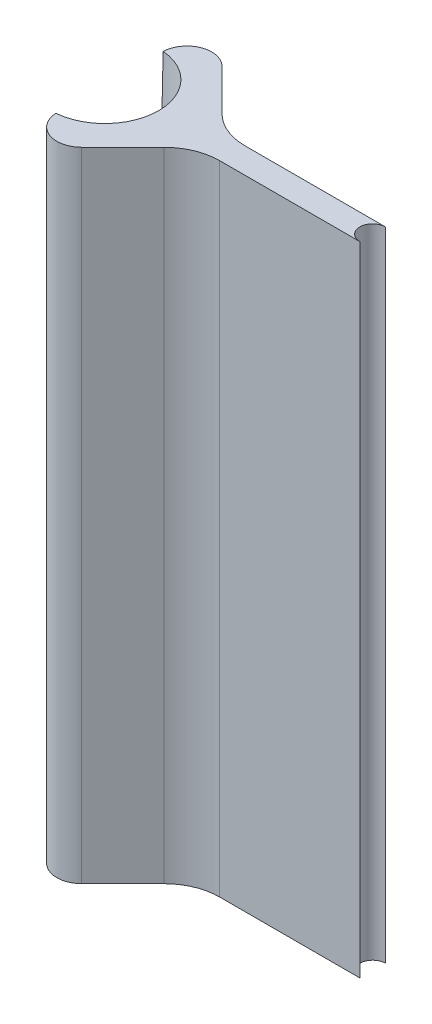
SolidWorks part; units mm, degrees
ref_plane "Front Plane" through (0, 0, 0) normal (0, 0, 1) x (1, 0, 0)
ref_plane "Top Plane" through (0, 0, 0) normal (0, 1, 0) x (1, 0, 0)
ref_plane "Right Plane" through (0, 0, 0) normal (1, 0, 0) x (0, 0, -1)
sketch "Sketch2" plane through (0, 0, 0) normal (0, 1, 0) x (1, 0, 0)
  line L0 (0, 0) -> (4, 0) construction
  line L1 (0, 0) -> (0.0553, 0.6326) construction
  line L2 (0.0553, 0.6326) -> (0.0751, 0.8586)
  line L3 (0.7385, 1.1) -> (1.3828, 0.4556)
  line L5 (4, 0.2) -> (4, 0) construction
  line L7 (0.7385, -1.1) -> (1.3828, -0.4556)
  line L8 (0.0553, -0.6326) -> (0.0751, -0.8586)
  line L9 (0.0553, 0.6326) -> (0.0553, -0.6326)
  line L15 (0, 0) -> (0.9192, -0.9192) construction
  line L16 (2, -0.2) -> (4.2, -0.2)
  line L19 (2, 0.2) -> (4.2, 0.2)
  circle A0 centre (0, 0) radius 0.635 construction
  arc A2 (0.0751, 0.8586) -> (0.7385, 1.1) centre (0.4631, 0.8246) cw
  arc A3 (1.3828, 0.4556) -> (2, 0.2) centre (2, 1.0728) ccw
  arc A4 (1.3828, -0.4556) -> (2, -0.2) centre (2, -1.0728) cw
  arc A5 (0.0751, -0.8586) -> (0.7385, -1.1) centre (0.4631, -0.8246) ccw
  arc A8 (4.2, 0.2) -> (4.2, -0.2) centre (4.2, 0) ccw
  point P16 (4.2928, -0.2)
  point P19 (3.8812, -0.2)
  point P26 (0, 0)
  point P27 (4, -0.2)
  point P28 (0, 0)
  point P29 (0, 0)
  dimension "D1" = 1.27
  dimension "D7" = 1.1
  dimension "D5" = 1.3
  dimension "D2" = 4
  dimension "D3" = 95
  dimension "D4" = 0.2
  dimension "D6" = 45
  dimension "D8" = 2
  dimension "D9" = 0.8246
extrude "Boss-Extrude2" add sketch "Sketch2" along normal blind 10
sketch "Sketch5" plane through (0, 0, 0) normal (0, -1, 0) x (1, 0, 0)
  circle A0 centre (0, 0) radius 0.635
  circle A1 centre (0, 0) radius 0.635 construction
extrude "Cut-Extrude1" cut sketch "Sketch5" against normal up to next (10 mm away) draft 1.2 draft outward yes
